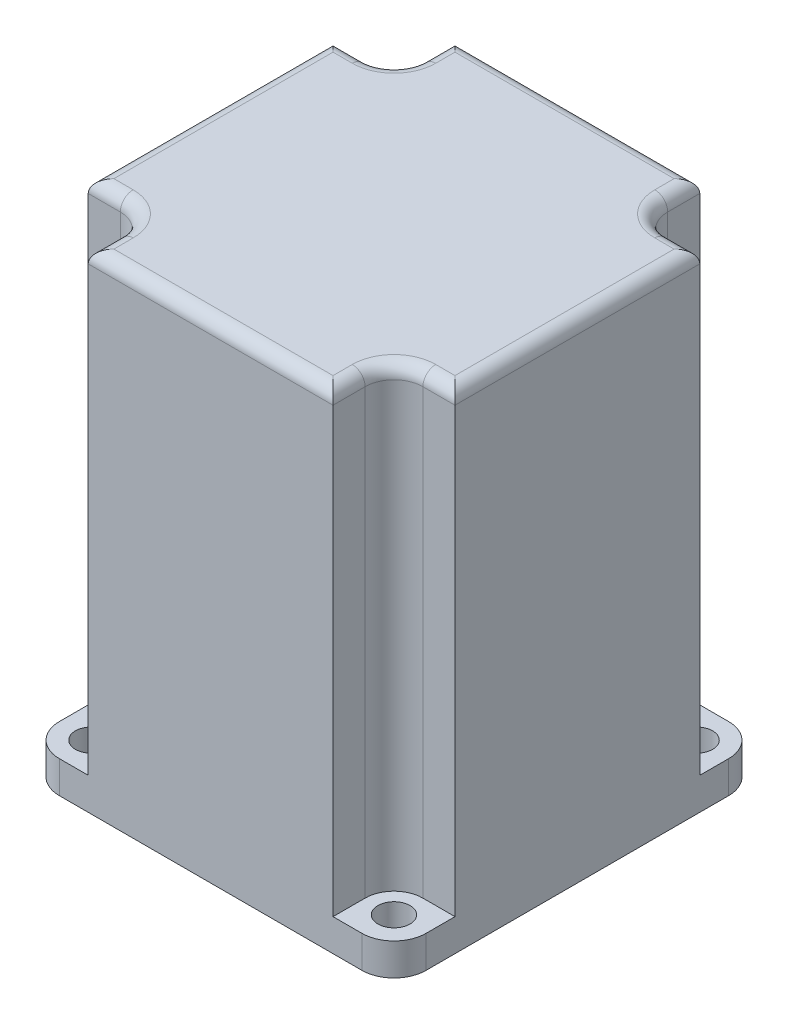
SolidWorks part; units mm, degrees
ref_plane "Płaszczyzna przednia" through (0, 0, 0) normal (0, 0, 1) x (1, 0, 0)
ref_plane "Płaszczyzna górna" through (0, 0, 0) normal (0, 1, 0) x (1, 0, 0)
ref_plane "Płaszczyzna prawa" through (0, 0, 0) normal (1, 0, 0) x (0, 0, -1)
sketch "Szkic1" plane through (0, 0, 0) normal (0, 1, 0) x (1, 0, 0)
  line L0 (-28.57, -28.57) -> (-28.57, 28.57)
  line L1 (-23.57, -23.57) -> (23.57, -23.57)
  line L2 (-23.57, -23.57) -> (-23.57, 23.57)
  line L3 (-23.57, 23.57) -> (23.57, 23.57)
  line L4 (23.57, -23.57) -> (23.57, 23.57)
  line L5 (-23.57, -23.57) -> (23.57, 23.57) construction
  line L6 (-23.57, 23.57) -> (23.57, -23.57) construction
  line L7 (-28.57, 28.57) -> (28.57, 28.57)
  line L8 (28.57, -28.57) -> (28.57, 28.57)
  line L9 (-28.57, -28.57) -> (28.57, -28.57)
  circle A0 centre (-23.57, 23.57) radius 2.5
  circle A1 centre (23.57, 23.57) radius 2.5
  circle A2 centre (23.57, -23.57) radius 2.5
  circle A3 centre (-23.57, -23.57) radius 2.5
  point P0 (0, 0)
  dimension "D3" = 5
  dimension "D1" = 47.14
  dimension "D2" = 5
extrude "Dodanie-wyciągnięcie1" add sketch "Szkic1" along normal blind 5 contours L0 L9 L8 L7 A3 L2 A0 L3 A1 L4 A2 L1 | A3 L1 A2 L4 A1 L3 A0 L2
sketch "Szkic2" plane through (0, 5, 0) normal (0, 1, 0) x (1, 0, 0)
  line L0 (-23.57, 19.07) -> (-28.57, 19.07)
  line L1 (-28.57, -28.57) -> (-28.57, 28.57) construction
  line L2 (-19.07, 23.57) -> (-19.07, 28.57)
  line L3 (-28.57, 28.57) -> (28.57, 28.57) construction
  line L4 (-23.57, -19.07) -> (-28.57, -19.07)
  line L5 (-19.07, -23.57) -> (-19.07, -28.57)
  line L6 (-28.57, -28.57) -> (28.57, -28.57) construction
  line L7 (19.07, -23.57) -> (19.07, -28.57)
  line L8 (23.57, -19.07) -> (28.57, -19.07)
  line L9 (28.57, -28.57) -> (28.57, 28.57) construction
  line L10 (19.07, 23.57) -> (19.07, 28.57)
  line L11 (23.57, 19.07) -> (28.57, 19.07)
  line L12 (-19.07, -28.57) -> (19.07, -28.57)
  line L13 (28.57, 19.07) -> (28.57, -19.07)
  line L14 (-19.07, 28.57) -> (19.07, 28.57)
  line L15 (-28.57, 19.07) -> (-28.57, -19.07)
  circle A8 centre (-23.57, 23.57) radius 4.5
  arc A9 (-23.57, 19.07) -> (-19.07, 23.57) centre (-23.57, 23.57) ccw
  circle A17 centre (23.57, 23.57) radius 4.5
  arc A18 (19.07, 23.57) -> (23.57, 19.07) centre (23.57, 23.57) ccw
  circle A20 centre (-23.57, -23.57) radius 4.5
  arc A21 (-19.07, -23.57) -> (-23.57, -19.07) centre (-23.57, -23.57) ccw
  circle A23 centre (23.57, -23.57) radius 4.5
  arc A24 (23.57, -19.07) -> (19.07, -23.57) centre (23.57, -23.57) ccw
  dimension "D4" = 2
  dimension "D1" = 2
  dimension "D2" = 2
  dimension "D3" = 2
extrude "Dodanie-wyciągnięcie2" add sketch "Szkic2" along normal blind 71
fillet "Zaokrąglenie1" radius 2 16 edges at (19.07, 76, 26.07) (0, 76, 28.57) (-19.07, 76, 26.07) (-20.388, 76, 20.388) (-26.07, 76, 19.07) (-28.57, 76, 0) (-26.07, 76, -19.07) (-20.388, 76, -20.388) (-19.07, 76, -26.07) (0, 76, -28.57) (19.07, 76, -26.07) (20.388, 76, -20.388) (26.07, 76, -19.07) (28.57, 76, 0) (26.07, 76, 19.07) (20.388, 76, 20.388)
sketch "Szkic3" plane through (0, 0, 0) normal (0, -1, 0) x (-1, 0, 0)
  circle A0 centre (0, 0) radius 4
  dimension "D1" = 8
extrude "Dodanie-wyciągnięcie3" add sketch "Szkic3" along normal blind 20.6
fillet "Zaokrąglenie2" radius 5 4 edges at (-28.57, 2.5, -28.57) (28.57, 2.5, -28.57) (28.57, 2.5, 28.57) (-28.57, 2.5, 28.57)
